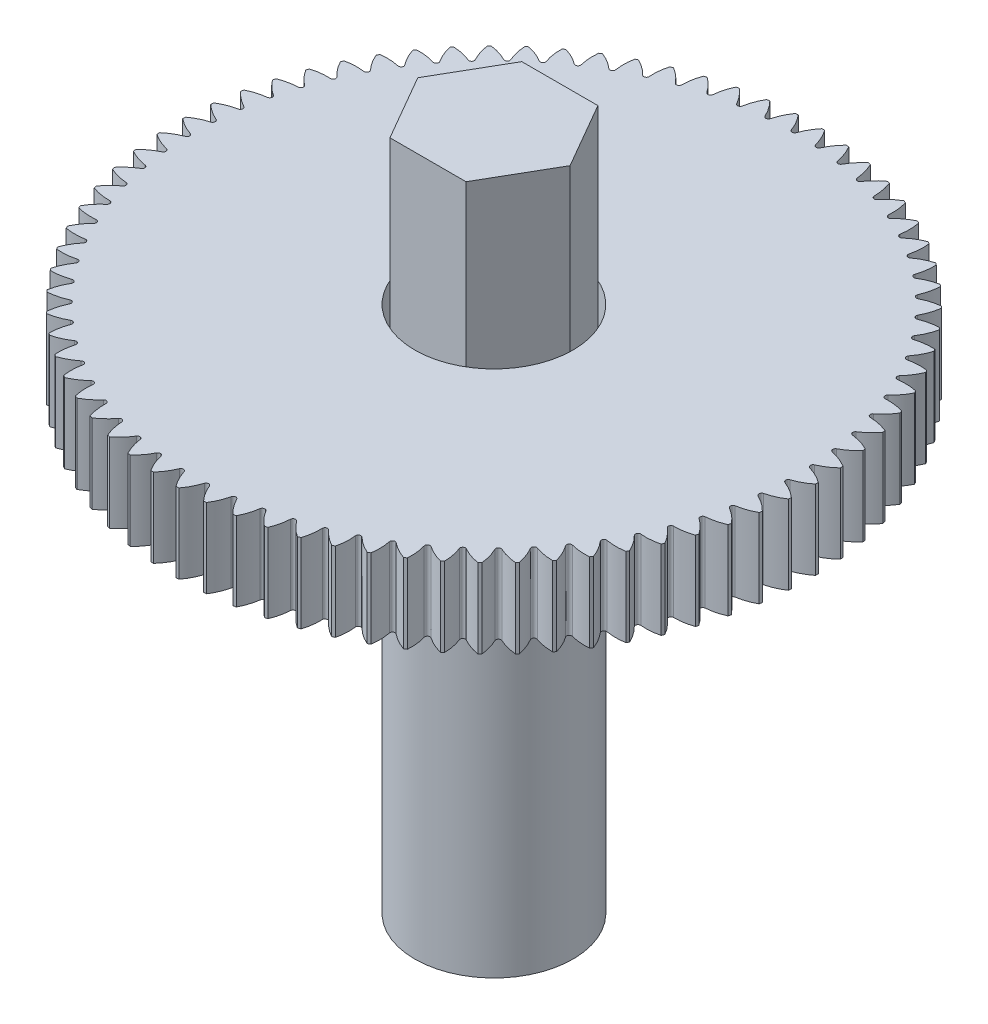
SolidWorks part; units mm, degrees
ref_plane "Front Plane" through (0, 0, 0) normal (0, 0, 1) x (1, 0, 0)
ref_plane "Top Plane" through (0, 0, 0) normal (0, 1, 0) x (1, 0, 0)
ref_plane "Right Plane" through (0, 0, 0) normal (1, 0, 0) x (0, 0, -1)
sketch "Sketch1" plane through (0, 0, 0) normal (0, 0, 1) x (1, 0, 0)
  line L0 (0, 13) -> (0, -13)
  line L1 (0, -13) -> (3, -13)
  line L2 (3, -13) -> (3, 4)
  line L3 (3, 4) -> (12, 4)
  line L4 (12, 4) -> (12, 7)
  line L5 (12, 7) -> (3, 7)
  line L6 (3, 7) -> (3, 13)
  line L7 (3, 13) -> (0, 13)
  point P9 (0, 0)
  dimension "D1" = 9
  dimension "D2" = 9
  dimension "D3" = 3
  dimension "D4" = 3
  dimension "D5" = 26
  dimension "D6" = 17
revolve "Revolve1" add sketch "Sketch1" angle 360 about L0
sketch "Sketch2" plane through (0, 7, 0) normal (0, 1, 0) x (1, 0, 0)
  line L0 (0, 13.9414) -> (0, 0) construction
  line L1 (-0.45, 11.9916) -> (0, 10.9916) construction
  line L2 (0, 10.9916) -> (0.45, 11.9916) construction
  line L3 (1.1666, 13.8925) -> (0, 0) construction
  line L4 (2.325, 13.7461) -> (0, 0) construction
  line L5 (3.4671, 13.5034) -> (0, 0) construction
  line L6 (4.5849, 13.1659) -> (0, 0) construction
  line L7 (5.6705, 12.7361) -> (0, 0) construction
  line L8 (6.7163, 12.2169) -> (0, 0) construction
  line L9 (7.715, 11.6121) -> (0, 0) construction
  line L10 (8.6597, 10.9258) -> (0, 0) construction
  line L11 (9.5435, 10.1628) -> (0, 0) construction
  line L12 (10.3605, 9.3286) -> (0, 0) construction
  line L13 (11.1047, 8.4289) -> (0, 0) construction
  line L14 (11.7711, 7.4702) -> (0, 0) construction
  line L15 (12.3549, 6.459) -> (0, 0) construction
  line L16 (12.852, 5.4025) -> (0, 0) construction
  line L17 (13.259, 4.3081) -> (0, 0) construction
  line L18 (13.573, 3.1835) -> (0, 0) construction
  line L19 (13.7918, 2.0366) -> (0, 0) construction
  line L20 (13.9139, 0.8754) -> (0, 0) construction
  line L21 (13.9383, -0.292) -> (0, 0) construction
  line L22 (13.865, -1.4573) -> (0, 0) construction
  line L23 (13.6944, -2.6124) -> (0, 0) construction
  line L24 (13.4278, -3.7491) -> (0, 0) construction
  line L25 (13.067, -4.8596) -> (0, 0) construction
  line L26 (12.6145, -5.9359) -> (0, 0) construction
  line L27 (12.0736, -6.9707) -> (0, 0) construction
  line L28 (11.4479, -7.9565) -> (0, 0) construction
  line L29 (10.742, -8.8866) -> (0, 0) construction
  line L30 (9.9607, -9.7543) -> (0, 0) construction
  line L31 (9.1096, -10.5536) -> (0, 0) construction
  line L32 (8.1945, -11.2788) -> (0, 0) construction
  line L33 (7.222, -11.925) -> (0, 0) construction
  line L34 (6.1988, -12.4875) -> (0, 0) construction
  line L35 (5.1322, -12.9624) -> (0, 0) construction
  line L36 (4.0295, -13.3464) -> (0, 0) construction
  line L37 (2.8986, -13.6367) -> (0, 0) construction
  line L38 (1.7473, -13.8314) -> (0, 0) construction
  line L39 (0.5838, -13.9291) -> (0, 0) construction
  line L40 (-0.5838, -13.9291) -> (0, 0) construction
  line L41 (-1.7473, -13.8314) -> (0, 0) construction
  line L42 (-2.8986, -13.6367) -> (0, 0) construction
  line L43 (-4.0295, -13.3464) -> (0, 0) construction
  line L44 (-5.1322, -12.9624) -> (0, 0) construction
  line L45 (-6.1988, -12.4875) -> (0, 0) construction
  line L46 (-7.222, -11.925) -> (0, 0) construction
  line L47 (-8.1945, -11.2788) -> (0, 0) construction
  line L48 (-9.1096, -10.5536) -> (0, 0) construction
  line L49 (-9.9607, -9.7543) -> (0, 0) construction
  line L50 (-10.742, -8.8866) -> (0, 0) construction
  line L51 (-11.4479, -7.9565) -> (0, 0) construction
  line L52 (-12.0736, -6.9707) -> (0, 0) construction
  line L53 (-12.6145, -5.9359) -> (0, 0) construction
  line L54 (-13.067, -4.8596) -> (0, 0) construction
  line L55 (-13.4278, -3.7491) -> (0, 0) construction
  line L56 (-13.6944, -2.6124) -> (0, 0) construction
  line L57 (-13.865, -1.4573) -> (0, 0) construction
  line L58 (-13.9383, -0.292) -> (0, 0) construction
  line L59 (-13.9139, 0.8754) -> (0, 0) construction
  line L60 (-13.7918, 2.0366) -> (0, 0) construction
  line L61 (-13.573, 3.1835) -> (0, 0) construction
  line L62 (-13.259, 4.3081) -> (0, 0) construction
  line L63 (-12.852, 5.4025) -> (0, 0) construction
  line L64 (-12.3549, 6.459) -> (0, 0) construction
  line L65 (-11.7711, 7.4702) -> (0, 0) construction
  line L66 (-11.1047, 8.4289) -> (0, 0) construction
  line L67 (-10.3605, 9.3286) -> (0, 0) construction
  line L68 (-9.5435, 10.1628) -> (0, 0) construction
  line L69 (-8.6597, 10.9258) -> (0, 0) construction
  line L70 (-7.715, 11.6121) -> (0, 0) construction
  line L71 (-6.7163, 12.2169) -> (0, 0) construction
  line L72 (-5.6705, 12.7361) -> (0, 0) construction
  line L73 (-4.5849, 13.1659) -> (0, 0) construction
  line L74 (-3.4671, 13.5034) -> (0, 0) construction
  line L75 (-2.325, 13.7461) -> (0, 0) construction
  line L76 (-1.1666, 13.8925) -> (0, 0) construction
  arc A0 (-0.45, 11.9916) -> (-0.0942, 11.3714) centre (-1.979, 10.7023) cw
  circle A1 centre (0, 0) radius 12
  arc A2 (0.45, 11.9916) -> (-0.45, 11.9916) centre (0, 0) ccw
  arc A3 (0.45, 11.9916) -> (0.0942, 11.3714) centre (1.979, 10.7023) ccw
  arc A4 (-0.0942, 11.3714) -> (0.0942, 11.3714) centre (0, 11.4049) ccw
  arc A5 (1.4518, 11.9118) -> (0.555, 11.9872) centre (0, 0) ccw
  arc A6 (0.555, 11.9872) -> (0.8576, 11.3394) centre (-1.0765, 10.8303) cw
  arc A7 (0.8576, 11.3394) -> (1.0454, 11.3237) centre (0.9543, 11.3649) ccw
  arc A8 (1.4518, 11.9118) -> (1.0454, 11.3237) centre (2.8676, 10.4991) ccw
  arc A9 (2.4435, 11.7486) -> (1.5561, 11.8987) centre (0, 0) ccw
  arc A10 (1.5561, 11.8987) -> (1.8035, 11.2279) centre (-0.1664, 10.8824) cw
  arc A11 (1.8035, 11.2279) -> (1.9893, 11.1965) centre (1.902, 11.2452) ccw
  arc A12 (2.4435, 11.7486) -> (1.9893, 11.1965) centre (3.7361, 10.2224) ccw
  arc A13 (3.418, 11.5029) -> (2.5463, 11.7267) centre (0, 0) ccw
  arc A14 (2.5463, 11.7267) -> (2.7367, 11.0376) centre (0.7448, 10.8582) cw
  arc A15 (2.7367, 11.0376) -> (2.9192, 10.9908) centre (2.8363, 11.0466) ccw
  arc A16 (3.418, 11.5029) -> (2.9192, 10.9908) centre (4.5783, 9.8739) ccw
  arc A17 (4.3686, 11.1766) -> (3.5187, 11.4725) centre (0, 0) ccw
  arc A18 (3.5187, 11.4725) -> (3.6507, 10.7699) centre (1.6507, 10.7578) cw
  arc A19 (3.6507, 10.7699) -> (3.8287, 10.7079) centre (3.7507, 10.7705) ccw
  arc A20 (4.3686, 11.1766) -> (3.8287, 10.7079) centre (5.3885, 9.4562) ccw
  arc A21 (5.2885, 10.7718) -> (4.4663, 11.1379) centre (0, 0) ccw
  arc A22 (4.4663, 11.1379) -> (4.5391, 10.4267) centre (2.5451, 10.5819) cw
  arc A23 (4.5391, 10.4267) -> (4.7113, 10.35) centre (4.6388, 10.4189) ccw
  arc A24 (5.2885, 10.7718) -> (4.7113, 10.35) centre (6.1609, 8.9721) ccw
  arc A25 (6.1713, 10.2915) -> (5.3826, 10.7251) centre (0, 0) ccw
  arc A26 (5.3826, 10.7251) -> (5.3957, 10.0103) centre (3.4217, 10.3318) cw
  arc A27 (5.3957, 10.0103) -> (5.5608, 9.9195) centre (5.4944, 9.9942) ccw
  arc A28 (6.1713, 10.2915) -> (5.5608, 9.9195) centre (6.89, 8.4251) ccw
  arc A29 (7.0108, 9.739) -> (6.2612, 10.2371) centre (0, 0) ccw
  arc A30 (6.2612, 10.2371) -> (6.2144, 9.5237) centre (4.2742, 10.0093) cw
  arc A31 (6.2144, 9.5237) -> (6.3714, 9.4194) centre (6.3114, 9.4994) ccw
  arc A32 (7.0108, 9.739) -> (6.3714, 9.4194) centre (7.5709, 7.819) ccw
  arc A33 (7.8012, 9.1182) -> (7.0959, 9.6772) centre (0, 0) ccw
  arc A34 (7.0959, 9.6772) -> (6.9895, 8.9703) centre (5.0968, 9.6165) cw
  arc A35 (6.9895, 8.9703) -> (7.1372, 8.8532) centre (7.0841, 8.9379) ccw
  arc A36 (7.8012, 9.1182) -> (7.1372, 8.8532) centre (8.1986, 7.1581) ccw
  arc A37 (8.5368, 8.4334) -> (7.8808, 9.0495) centre (0, 0) ccw
  arc A38 (7.8808, 9.0495) -> (7.7156, 8.3539) centre (5.8836, 9.1563) cw
  arc A39 (7.7156, 8.3539) -> (7.853, 8.2249) centre (7.8072, 8.3138) ccw
  arc A40 (8.5368, 8.4334) -> (7.853, 8.2249) centre (8.7688, 6.4469) ccw
  arc A41 (9.2126, 7.6895) -> (8.6104, 8.3583) centre (0, 0) ccw
  arc A42 (8.6104, 8.3583) -> (8.3876, 7.679) centre (6.6292, 8.6319) cw
  arc A43 (8.3876, 7.679) -> (8.5137, 7.5389) centre (8.4755, 7.6314) ccw
  arc A44 (9.2126, 7.6895) -> (8.5137, 7.5389) centre (9.2775, 5.6906) ccw
  arc A45 (9.8237, 6.8916) -> (9.2796, 7.6085) centre (0, 0) ccw
  arc A46 (9.2796, 7.6085) -> (9.0007, 6.9502) centre (7.3282, 8.0469) cw
  arc A47 (9.0007, 6.9502) -> (9.1147, 6.8001) centre (9.0843, 6.8954) ccw
  arc A48 (9.8237, 6.8916) -> (9.1147, 6.8001) centre (9.7212, 4.8943) ccw
  arc A49 (10.3659, 6.0455) -> (9.8837, 6.8053) centre (0, 0) ccw
  arc A50 (9.8837, 6.8053) -> (9.5507, 6.1727) centre (7.9758, 7.4055) cw
  arc A51 (9.5507, 6.1727) -> (9.6517, 6.0136) centre (9.6295, 6.1111) ccw
  arc A52 (10.3659, 6.0455) -> (9.6517, 6.0136) centre (10.0966, 4.0637) ccw
  arc A53 (10.8354, 5.1569) -> (10.4185, 5.9544) centre (0, 0) ccw
  arc A54 (10.4185, 5.9544) -> (10.0338, 5.3519) centre (8.5675, 6.7121) cw
  arc A55 (10.0338, 5.3519) -> (10.1211, 5.1848) centre (10.1071, 5.2838) ccw
  arc A56 (10.8354, 5.1569) -> (10.1211, 5.1848) centre (10.4012, 3.2046) ccw
  arc A57 (11.229, 4.2321) -> (10.8802, 5.0618) centre (0, 0) ccw
  arc A58 (10.8802, 5.0618) -> (10.4464, 4.4935) centre (9.0992, 5.9716) cw
  arc A59 (10.4464, 4.4935) -> (10.5194, 4.3197) centre (10.5138, 4.4196) ccw
  arc A60 (11.229, 4.2321) -> (10.5194, 4.3197) centre (10.6329, 2.323) ccw
  arc A61 (11.5437, 3.2776) -> (11.2656, 4.1336) centre (0, 0) ccw
  arc A62 (11.2656, 4.1336) -> (10.7858, 3.6036) centre (9.5669, 5.1893) cw
  arc A63 (10.7858, 3.6036) -> (10.844, 3.4243) centre (10.8467, 3.5243) ccw
  arc A64 (11.5437, 3.2776) -> (10.844, 3.4243) centre (10.79, 1.4251) ccw
  arc A65 (11.7775, 2.3002) -> (11.572, 3.1764) centre (0, 0) ccw
  arc A66 (11.572, 3.1764) -> (11.0495, 2.6884) centre (9.9676, 4.3706) cw
  arc A67 (11.0495, 2.6884) -> (11.0925, 2.5049) centre (11.1036, 2.6043) ccw
  arc A68 (11.7775, 2.3002) -> (11.0925, 2.5049) centre (10.8714, 0.5172) ccw
  arc A69 (11.9287, 1.3066) -> (11.7972, 2.1969) centre (0, 0) ccw
  arc A70 (11.7972, 2.1969) -> (11.2357, 1.7544) centre (10.2984, 3.5212) cw
  arc A71 (11.2357, 1.7544) -> (11.2632, 1.5679) centre (11.2826, 1.6661) ccw
  arc A72 (11.9287, 1.3066) -> (11.2632, 1.5679) centre (10.8766, -0.3943) ccw
  arc A73 (11.9962, 0.3038) -> (11.9396, 1.2021) centre (0, 0) ccw
  arc A74 (11.9396, 1.2021) -> (11.3431, 0.8081) centre (10.5569, 2.6471) cw
  arc A75 (11.3431, 0.8081) -> (11.3549, 0.62) centre (11.3824, 0.7161) ccw
  arc A76 (11.9962, 0.3038) -> (11.3549, 0.62) centre (10.8054, -1.3031) ccw
  arc A77 (11.9795, -0.701) -> (11.9984, 0.1988) centre (0, 0) ccw
  arc A78 (11.9984, 0.1988) -> (11.3709, -0.1439) centre (10.7414, 1.7544) cw
  arc A79 (11.3709, -0.1439) -> (11.367, -0.3324) centre (11.4024, -0.2388) ccw
  arc A80 (11.9795, -0.701) -> (11.367, -0.3324) centre (10.6585, -2.2027) ccw
  arc A81 (11.8788, -1.701) -> (11.9729, -0.8059) centre (0, 0) ccw
  arc A82 (11.9729, -0.8059) -> (11.319, -1.0949) centre (10.8505, 0.8494) cw
  arc A83 (11.319, -1.0949) -> (11.2993, -1.2824) centre (11.3424, -1.1921) ccw
  arc A84 (11.8788, -1.701) -> (11.2993, -1.2824) centre (10.4368, -3.0868) ccw
  arc A85 (11.6948, -2.689) -> (11.8635, -1.805) centre (0, 0) ccw
  arc A86 (11.8635, -1.805) -> (11.1877, -2.0382) centre (10.8835, -0.0615) cw
  arc A87 (11.1877, -2.0382) -> (11.1524, -2.2234) centre (11.2029, -2.1371) ccw
  arc A88 (11.6948, -2.689) -> (11.1524, -2.2234) centre (10.1419, -3.9493) ccw
  arc A89 (11.4288, -3.6582) -> (11.6708, -2.7913) centre (0, 0) ccw
  arc A90 (11.6708, -2.7913) -> (10.9779, -2.9672) centre (10.8402, -0.972) cw
  arc A91 (10.9779, -2.9672) -> (10.9272, -3.1488) centre (10.9848, -3.067) ccw
  arc A92 (11.4288, -3.6582) -> (10.9272, -3.1488) centre (9.7758, -4.7841) ccw
  arc A93 (11.0826, -4.6017) -> (11.3963, -3.7581) centre (0, 0) ccw
  arc A94 (11.3963, -3.7581) -> (10.6911, -3.8754) centre (10.7209, -1.8757) cw
  arc A95 (10.6911, -3.8754) -> (10.6254, -4.0521) centre (10.6896, -3.9754) ccw
  arc A96 (11.0826, -4.6017) -> (10.6254, -4.0521) centre (9.3412, -5.5854) ccw
  arc A97 (10.6587, -5.5129) -> (11.0419, -4.6986) centre (0, 0) ccw
  arc A98 (11.0419, -4.6986) -> (10.3293, -4.7565) centre (10.5263, -2.7662) cw
  arc A99 (10.3293, -4.7565) -> (10.2491, -4.927) centre (10.3195, -4.856) ccw
  arc A100 (10.6587, -5.5129) -> (10.2491, -4.927) centre (8.8411, -6.3474) ccw
  arc A101 (10.16, -6.3855) -> (10.61, -5.6061) centre (0, 0) ccw
  arc A102 (10.61, -5.6061) -> (9.8951, -5.6041) centre (10.2579, -3.6373) cw
  arc A103 (9.8951, -5.6041) -> (9.8008, -5.7673) centre (9.8769, -5.7025) ccw
  arc A104 (10.16, -6.3855) -> (9.8008, -5.7673) centre (8.279, -7.065) ccw
  arc A105 (9.59, -7.2133) -> (10.1037, -6.4742) centre (0, 0) ccw
  arc A106 (10.1037, -6.4742) -> (9.3914, -6.4125) centre (9.9176, -4.4829) cw
  arc A107 (9.3914, -6.4125) -> (9.2839, -6.5672) centre (9.3651, -6.5089) ccw
  arc A108 (9.59, -7.2133) -> (9.2839, -6.5672) centre (7.6587, -7.733) ccw
  arc A109 (8.9528, -7.9904) -> (9.5265, -7.297) centre (0, 0) ccw
  arc A110 (9.5265, -7.297) -> (8.8219, -7.1758) centre (9.5077, -5.2971) cw
  arc A111 (8.8219, -7.1758) -> (8.7018, -7.321) centre (8.7876, -7.2698) ccw
  arc A112 (8.9528, -7.9904) -> (8.7018, -7.321) centre (6.9848, -8.3467) ccw
  arc A113 (8.2528, -8.7116) -> (8.8825, -8.0685) centre (0, 0) ccw
  arc A114 (8.8825, -8.0685) -> (8.1905, -7.8889) centre (9.0311, -6.0741) cw
  arc A115 (8.1905, -7.8889) -> (8.0587, -8.0235) centre (8.1485, -7.9796) ccw
  arc A116 (8.2528, -8.7116) -> (8.0587, -8.0235) centre (6.2619, -8.9019) ccw
  arc A117 (7.4949, -9.3716) -> (8.1762, -8.7835) centre (0, 0) ccw
  arc A118 (8.1762, -8.7835) -> (7.5017, -8.5466) centre (8.4912, -6.8085) cw
  arc A119 (7.5017, -8.5466) -> (7.359, -8.6697) centre (7.4522, -8.6335) ccw
  arc A120 (7.4949, -9.3716) -> (7.359, -8.6697) centre (5.495, -9.3947) ccw
  arc A121 (6.6844, -9.9659) -> (7.4125, -9.4369) centre (0, 0) ccw
  arc A122 (7.4125, -9.4369) -> (6.7602, -9.1443) centre (7.8917, -7.4951) cw
  arc A123 (6.7602, -9.1443) -> (6.6077, -9.2551) centre (6.7036, -9.2268) ccw
  arc A124 (6.6844, -9.9659) -> (6.6077, -9.2551) centre (4.6896, -9.8215) ccw
  arc A125 (5.827, -10.4903) -> (6.5969, -10.024) centre (0, 0) ccw
  arc A126 (6.5969, -10.024) -> (5.9713, -9.6779) centre (7.2368, -8.1292) cw
  arc A127 (5.9713, -9.6779) -> (5.8101, -9.7755) centre (5.908, -9.7553) ccw
  arc A128 (5.827, -10.4903) -> (5.8101, -9.7755) centre (3.8513, -10.1795) ccw
  arc A129 (4.9288, -10.9411) -> (5.7349, -10.5409) centre (0, 0) ccw
  arc A130 (5.7349, -10.5409) -> (5.1406, -10.1436) centre (6.5312, -8.7062) cw
  arc A131 (5.1406, -10.1436) -> (4.9717, -10.2274) centre (5.071, -10.2155) ccw
  arc A132 (4.9288, -10.9411) -> (4.9717, -10.2274) centre (2.986, -10.4661) ccw
  arc A133 (3.996, -11.3151) -> (4.8328, -10.9838) centre (0, 0) ccw
  arc A134 (4.8328, -10.9838) -> (4.2737, -10.5382) centre (5.7798, -9.2222) cw
  arc A135 (4.2737, -10.5382) -> (4.0985, -10.6076) centre (4.1984, -10.604) ccw
  arc A136 (3.996, -11.3151) -> (4.0985, -10.6076) centre (2.0998, -10.6792) ccw
  arc A137 (3.0351, -11.6098) -> (3.8967, -11.3497) centre (0, 0) ccw
  arc A138 (3.8967, -11.3497) -> (3.3769, -10.8589) centre (4.9878, -9.6735) cw
  arc A139 (3.3769, -10.8589) -> (3.1965, -10.9133) centre (3.2964, -10.9181) ccw
  arc A140 (3.0351, -11.6098) -> (3.1965, -10.9133) centre (1.1988, -10.8175) ccw
  arc A141 (2.053, -11.8231) -> (2.9334, -11.636) centre (0, 0) ccw
  arc A142 (2.9334, -11.636) -> (2.4564, -11.1034) centre (4.1609, -10.057) cw
  arc A143 (2.4564, -11.1034) -> (2.2721, -11.1425) centre (2.3712, -11.1557) ccw
  arc A144 (2.053, -11.8231) -> (2.2721, -11.1425) centre (0.2894, -10.8799) ccw
  arc A145 (1.0565, -11.9534) -> (1.9494, -11.8406) centre (0, 0) ccw
  arc A146 (1.9494, -11.8406) -> (1.5187, -11.27) centre (3.3047, -10.3699) cw
  arc A147 (1.5187, -11.27) -> (1.3317, -11.2936) centre (1.4294, -11.315) ccw
  arc A148 (1.0565, -11.9534) -> (1.3317, -11.2936) centre (-0.622, -10.8659) ccw
  arc A149 (0.0525, -11.9999) -> (0.9518, -11.9622) centre (0, 0) ccw
  arc A150 (0.9518, -11.9622) -> (0.5703, -11.3575) centre (2.4254, -10.61) cw
  arc A151 (0.5703, -11.3575) -> (0.382, -11.3654) centre (0.4776, -11.3949) ccw
  arc A152 (0.0525, -11.9999) -> (0.382, -11.3654) centre (-1.5291, -10.7758) ccw
  arc A153 (-0.9518, -11.9622) -> (-0.0525, -11.9999) centre (0, 0) ccw
  arc A154 (-0.0525, -11.9999) -> (-0.382, -11.3654) centre (1.5291, -10.7758) cw
  arc A155 (-0.382, -11.3654) -> (-0.5703, -11.3575) centre (-0.4776, -11.3949) ccw
  arc A156 (-0.9518, -11.9622) -> (-0.5703, -11.3575) centre (-2.4254, -10.61) ccw
  arc A157 (-1.9494, -11.8406) -> (-1.0565, -11.9534) centre (0, 0) ccw
  arc A158 (-1.0565, -11.9534) -> (-1.3317, -11.2936) centre (0.622, -10.8659) cw
  arc A159 (-1.3317, -11.2936) -> (-1.5187, -11.27) centre (-1.4294, -11.315) ccw
  arc A160 (-1.9494, -11.8406) -> (-1.5187, -11.27) centre (-3.3047, -10.3699) ccw
  arc A161 (-2.9334, -11.636) -> (-2.053, -11.8231) centre (0, 0) ccw
  arc A162 (-2.053, -11.8231) -> (-2.2721, -11.1425) centre (-0.2894, -10.8799) cw
  arc A163 (-2.2721, -11.1425) -> (-2.4564, -11.1034) centre (-2.3712, -11.1557) ccw
  arc A164 (-2.9334, -11.636) -> (-2.4564, -11.1034) centre (-4.1609, -10.057) ccw
  arc A165 (-3.8967, -11.3497) -> (-3.0351, -11.6098) centre (0, 0) ccw
  arc A166 (-3.0351, -11.6098) -> (-3.1965, -10.9133) centre (-1.1988, -10.8175) cw
  arc A167 (-3.1965, -10.9133) -> (-3.3769, -10.8589) centre (-3.2964, -10.9181) ccw
  arc A168 (-3.8967, -11.3497) -> (-3.3769, -10.8589) centre (-4.9878, -9.6735) ccw
  arc A169 (-4.8328, -10.9838) -> (-3.996, -11.3151) centre (0, 0) ccw
  arc A170 (-3.996, -11.3151) -> (-4.0985, -10.6076) centre (-2.0998, -10.6792) cw
  arc A171 (-4.0985, -10.6076) -> (-4.2737, -10.5382) centre (-4.1984, -10.604) ccw
  arc A172 (-4.8328, -10.9838) -> (-4.2737, -10.5382) centre (-5.7798, -9.2222) ccw
  arc A173 (-5.7349, -10.5409) -> (-4.9288, -10.9411) centre (0, 0) ccw
  arc A174 (-4.9288, -10.9411) -> (-4.9717, -10.2274) centre (-2.986, -10.4661) cw
  arc A175 (-4.9717, -10.2274) -> (-5.1406, -10.1436) centre (-5.071, -10.2155) ccw
  arc A176 (-5.7349, -10.5409) -> (-5.1406, -10.1436) centre (-6.5312, -8.7062) ccw
  arc A177 (-6.5969, -10.024) -> (-5.827, -10.4903) centre (0, 0) ccw
  arc A178 (-5.827, -10.4903) -> (-5.8101, -9.7755) centre (-3.8513, -10.1795) cw
  arc A179 (-5.8101, -9.7755) -> (-5.9713, -9.6779) centre (-5.908, -9.7553) ccw
  arc A180 (-6.5969, -10.024) -> (-5.9713, -9.6779) centre (-7.2368, -8.1292) ccw
  arc A181 (-7.4125, -9.4369) -> (-6.6844, -9.9659) centre (0, 0) ccw
  arc A182 (-6.6844, -9.9659) -> (-6.6077, -9.2551) centre (-4.6896, -9.8215) cw
  arc A183 (-6.6077, -9.2551) -> (-6.7602, -9.1443) centre (-6.7036, -9.2268) ccw
  arc A184 (-7.4125, -9.4369) -> (-6.7602, -9.1443) centre (-7.8917, -7.4951) ccw
  arc A185 (-8.1762, -8.7835) -> (-7.4949, -9.3716) centre (0, 0) ccw
  arc A186 (-7.4949, -9.3716) -> (-7.359, -8.6697) centre (-5.495, -9.3947) cw
  arc A187 (-7.359, -8.6697) -> (-7.5017, -8.5466) centre (-7.4522, -8.6335) ccw
  arc A188 (-8.1762, -8.7835) -> (-7.5017, -8.5466) centre (-8.4912, -6.8085) ccw
  arc A189 (-8.8825, -8.0685) -> (-8.2528, -8.7116) centre (0, 0) ccw
  arc A190 (-8.2528, -8.7116) -> (-8.0587, -8.0235) centre (-6.2619, -8.9019) cw
  arc A191 (-8.0587, -8.0235) -> (-8.1905, -7.8889) centre (-8.1485, -7.9796) ccw
  arc A192 (-8.8825, -8.0685) -> (-8.1905, -7.8889) centre (-9.0311, -6.0741) ccw
  arc A193 (-9.5265, -7.297) -> (-8.9528, -7.9904) centre (0, 0) ccw
  arc A194 (-8.9528, -7.9904) -> (-8.7018, -7.321) centre (-6.9848, -8.3467) cw
  arc A195 (-8.7018, -7.321) -> (-8.8219, -7.1758) centre (-8.7876, -7.2698) ccw
  arc A196 (-9.5265, -7.297) -> (-8.8219, -7.1758) centre (-9.5077, -5.2971) ccw
  arc A197 (-10.1037, -6.4742) -> (-9.59, -7.2133) centre (0, 0) ccw
  arc A198 (-9.59, -7.2133) -> (-9.2839, -6.5672) centre (-7.6587, -7.733) cw
  arc A199 (-9.2839, -6.5672) -> (-9.3914, -6.4125) centre (-9.3651, -6.5089) ccw
  arc A200 (-10.1037, -6.4742) -> (-9.3914, -6.4125) centre (-9.9176, -4.4829) ccw
  arc A201 (-10.61, -5.6061) -> (-10.16, -6.3855) centre (0, 0) ccw
  arc A202 (-10.16, -6.3855) -> (-9.8008, -5.7673) centre (-8.279, -7.065) cw
  arc A203 (-9.8008, -5.7673) -> (-9.8951, -5.6041) centre (-9.8769, -5.7025) ccw
  arc A204 (-10.61, -5.6061) -> (-9.8951, -5.6041) centre (-10.2579, -3.6373) ccw
  arc A205 (-11.0419, -4.6986) -> (-10.6587, -5.5129) centre (0, 0) ccw
  arc A206 (-10.6587, -5.5129) -> (-10.2491, -4.927) centre (-8.8411, -6.3474) cw
  arc A207 (-10.2491, -4.927) -> (-10.3293, -4.7565) centre (-10.3195, -4.856) ccw
  arc A208 (-11.0419, -4.6986) -> (-10.3293, -4.7565) centre (-10.5263, -2.7662) ccw
  arc A209 (-11.3963, -3.7581) -> (-11.0826, -4.6017) centre (0, 0) ccw
  arc A210 (-11.0826, -4.6017) -> (-10.6254, -4.0521) centre (-9.3412, -5.5854) cw
  arc A211 (-10.6254, -4.0521) -> (-10.6911, -3.8754) centre (-10.6896, -3.9754) ccw
  arc A212 (-11.3963, -3.7581) -> (-10.6911, -3.8754) centre (-10.7209, -1.8757) ccw
  arc A213 (-11.6708, -2.7913) -> (-11.4288, -3.6582) centre (0, 0) ccw
  arc A214 (-11.4288, -3.6582) -> (-10.9272, -3.1488) centre (-9.7758, -4.7841) cw
  arc A215 (-10.9272, -3.1488) -> (-10.9779, -2.9672) centre (-10.9848, -3.067) ccw
  arc A216 (-11.6708, -2.7913) -> (-10.9779, -2.9672) centre (-10.8402, -0.972) ccw
  arc A217 (-11.8635, -1.805) -> (-11.6948, -2.689) centre (0, 0) ccw
  arc A218 (-11.6948, -2.689) -> (-11.1524, -2.2234) centre (-10.1419, -3.9493) cw
  arc A219 (-11.1524, -2.2234) -> (-11.1877, -2.0382) centre (-11.2029, -2.1371) ccw
  arc A220 (-11.8635, -1.805) -> (-11.1877, -2.0382) centre (-10.8835, -0.0615) ccw
  arc A221 (-11.9729, -0.8059) -> (-11.8788, -1.701) centre (0, 0) ccw
  arc A222 (-11.8788, -1.701) -> (-11.2993, -1.2824) centre (-10.4368, -3.0868) cw
  arc A223 (-11.2993, -1.2824) -> (-11.319, -1.0949) centre (-11.3424, -1.1921) ccw
  arc A224 (-11.9729, -0.8059) -> (-11.319, -1.0949) centre (-10.8505, 0.8494) ccw
  arc A225 (-11.9984, 0.1988) -> (-11.9795, -0.701) centre (0, 0) ccw
  arc A226 (-11.9795, -0.701) -> (-11.367, -0.3324) centre (-10.6585, -2.2027) cw
  arc A227 (-11.367, -0.3324) -> (-11.3709, -0.1439) centre (-11.4024, -0.2388) ccw
  arc A228 (-11.9984, 0.1988) -> (-11.3709, -0.1439) centre (-10.7414, 1.7544) ccw
  arc A229 (-11.9396, 1.2021) -> (-11.9962, 0.3038) centre (0, 0) ccw
  arc A230 (-11.9962, 0.3038) -> (-11.3549, 0.62) centre (-10.8054, -1.3031) cw
  arc A231 (-11.3549, 0.62) -> (-11.3431, 0.8081) centre (-11.3824, 0.7161) ccw
  arc A232 (-11.9396, 1.2021) -> (-11.3431, 0.8081) centre (-10.5569, 2.6471) ccw
  arc A233 (-11.7972, 2.1969) -> (-11.9287, 1.3066) centre (0, 0) ccw
  arc A234 (-11.9287, 1.3066) -> (-11.2632, 1.5679) centre (-10.8766, -0.3943) cw
  arc A235 (-11.2632, 1.5679) -> (-11.2357, 1.7544) centre (-11.2826, 1.6661) ccw
  arc A236 (-11.7972, 2.1969) -> (-11.2357, 1.7544) centre (-10.2984, 3.5212) ccw
  arc A237 (-11.572, 3.1764) -> (-11.7775, 2.3002) centre (0, 0) ccw
  arc A238 (-11.7775, 2.3002) -> (-11.0925, 2.5049) centre (-10.8714, 0.5172) cw
  arc A239 (-11.0925, 2.5049) -> (-11.0495, 2.6884) centre (-11.1036, 2.6043) ccw
  arc A240 (-11.572, 3.1764) -> (-11.0495, 2.6884) centre (-9.9676, 4.3706) ccw
  arc A241 (-11.2656, 4.1336) -> (-11.5437, 3.2776) centre (0, 0) ccw
  arc A242 (-11.5437, 3.2776) -> (-10.844, 3.4243) centre (-10.79, 1.4251) cw
  arc A243 (-10.844, 3.4243) -> (-10.7858, 3.6036) centre (-10.8467, 3.5243) ccw
  arc A244 (-11.2656, 4.1336) -> (-10.7858, 3.6036) centre (-9.5669, 5.1893) ccw
  arc A245 (-10.8802, 5.0618) -> (-11.229, 4.2321) centre (0, 0) ccw
  arc A246 (-11.229, 4.2321) -> (-10.5194, 4.3197) centre (-10.6329, 2.323) cw
  arc A247 (-10.5194, 4.3197) -> (-10.4464, 4.4935) centre (-10.5138, 4.4196) ccw
  arc A248 (-10.8802, 5.0618) -> (-10.4464, 4.4935) centre (-9.0992, 5.9716) ccw
  arc A249 (-10.4185, 5.9544) -> (-10.8354, 5.1569) centre (0, 0) ccw
  arc A250 (-10.8354, 5.1569) -> (-10.1211, 5.1848) centre (-10.4012, 3.2046) cw
  arc A251 (-10.1211, 5.1848) -> (-10.0338, 5.3519) centre (-10.1071, 5.2838) ccw
  arc A252 (-10.4185, 5.9544) -> (-10.0338, 5.3519) centre (-8.5675, 6.7121) ccw
  arc A253 (-9.8837, 6.8053) -> (-10.3659, 6.0455) centre (0, 0) ccw
  arc A254 (-10.3659, 6.0455) -> (-9.6517, 6.0136) centre (-10.0966, 4.0637) cw
  arc A255 (-9.6517, 6.0136) -> (-9.5507, 6.1727) centre (-9.6295, 6.1111) ccw
  arc A256 (-9.8837, 6.8053) -> (-9.5507, 6.1727) centre (-7.9758, 7.4055) ccw
  arc A257 (-9.2796, 7.6085) -> (-9.8237, 6.8916) centre (0, 0) ccw
  arc A258 (-9.8237, 6.8916) -> (-9.1147, 6.8001) centre (-9.7212, 4.8943) cw
  arc A259 (-9.1147, 6.8001) -> (-9.0007, 6.9502) centre (-9.0843, 6.8954) ccw
  arc A260 (-9.2796, 7.6085) -> (-9.0007, 6.9502) centre (-7.3282, 8.0469) ccw
  arc A261 (-8.6104, 8.3583) -> (-9.2126, 7.6895) centre (0, 0) ccw
  arc A262 (-9.2126, 7.6895) -> (-8.5137, 7.5389) centre (-9.2775, 5.6906) cw
  arc A263 (-8.5137, 7.5389) -> (-8.3876, 7.679) centre (-8.4755, 7.6314) ccw
  arc A264 (-8.6104, 8.3583) -> (-8.3876, 7.679) centre (-6.6292, 8.6319) ccw
  arc A265 (-7.8808, 9.0495) -> (-8.5368, 8.4334) centre (0, 0) ccw
  arc A266 (-8.5368, 8.4334) -> (-7.853, 8.2249) centre (-8.7688, 6.4469) cw
  arc A267 (-7.853, 8.2249) -> (-7.7156, 8.3539) centre (-7.8072, 8.3138) ccw
  arc A268 (-7.8808, 9.0495) -> (-7.7156, 8.3539) centre (-5.8836, 9.1563) ccw
  arc A269 (-7.0959, 9.6772) -> (-7.8012, 9.1182) centre (0, 0) ccw
  arc A270 (-7.8012, 9.1182) -> (-7.1372, 8.8532) centre (-8.1986, 7.1581) cw
  arc A271 (-7.1372, 8.8532) -> (-6.9895, 8.9703) centre (-7.0841, 8.9379) ccw
  arc A272 (-7.0959, 9.6772) -> (-6.9895, 8.9703) centre (-5.0968, 9.6165) ccw
  arc A273 (-6.2612, 10.2371) -> (-7.0108, 9.739) centre (0, 0) ccw
  arc A274 (-7.0108, 9.739) -> (-6.3714, 9.4194) centre (-7.5709, 7.819) cw
  arc A275 (-6.3714, 9.4194) -> (-6.2144, 9.5237) centre (-6.3114, 9.4994) ccw
  arc A276 (-6.2612, 10.2371) -> (-6.2144, 9.5237) centre (-4.2742, 10.0093) ccw
  arc A277 (-5.3826, 10.7251) -> (-6.1713, 10.2915) centre (0, 0) ccw
  arc A278 (-6.1713, 10.2915) -> (-5.5608, 9.9195) centre (-6.89, 8.4251) cw
  arc A279 (-5.5608, 9.9195) -> (-5.3957, 10.0103) centre (-5.4944, 9.9942) ccw
  arc A280 (-5.3826, 10.7251) -> (-5.3957, 10.0103) centre (-3.4217, 10.3318) ccw
  arc A281 (-4.4663, 11.1379) -> (-5.2885, 10.7718) centre (0, 0) ccw
  arc A282 (-5.2885, 10.7718) -> (-4.7113, 10.35) centre (-6.1609, 8.9721) cw
  arc A283 (-4.7113, 10.35) -> (-4.5391, 10.4267) centre (-4.6388, 10.4189) ccw
  arc A284 (-4.4663, 11.1379) -> (-4.5391, 10.4267) centre (-2.5451, 10.5819) ccw
  arc A285 (-3.5187, 11.4725) -> (-4.3686, 11.1766) centre (0, 0) ccw
  arc A286 (-4.3686, 11.1766) -> (-3.8287, 10.7079) centre (-5.3885, 9.4562) cw
  arc A287 (-3.8287, 10.7079) -> (-3.6507, 10.7699) centre (-3.7507, 10.7705) ccw
  arc A288 (-3.5187, 11.4725) -> (-3.6507, 10.7699) centre (-1.6507, 10.7578) ccw
  arc A289 (-2.5463, 11.7267) -> (-3.418, 11.5029) centre (0, 0) ccw
  arc A290 (-3.418, 11.5029) -> (-2.9192, 10.9908) centre (-4.5783, 9.8739) cw
  arc A291 (-2.9192, 10.9908) -> (-2.7367, 11.0376) centre (-2.8363, 11.0466) ccw
  arc A292 (-2.5463, 11.7267) -> (-2.7367, 11.0376) centre (-0.7448, 10.8582) ccw
  arc A293 (-1.5561, 11.8987) -> (-2.4435, 11.7486) centre (0, 0) ccw
  arc A294 (-2.4435, 11.7486) -> (-1.9893, 11.1965) centre (-3.7361, 10.2224) cw
  arc A295 (-1.9893, 11.1965) -> (-1.8035, 11.2279) centre (-1.902, 11.2452) ccw
  arc A296 (-1.5561, 11.8987) -> (-1.8035, 11.2279) centre (0.1664, 10.8824) ccw
  arc A297 (-0.555, 11.9872) -> (-1.4518, 11.9118) centre (0, 0) ccw
  arc A298 (-1.4518, 11.9118) -> (-1.0454, 11.3237) centre (-2.8676, 10.4991) cw
  arc A299 (-1.0454, 11.3237) -> (-0.8576, 11.3394) centre (-0.9543, 11.3649) ccw
  arc A300 (-0.555, 11.9872) -> (-0.8576, 11.3394) centre (1.0765, 10.8303) ccw
  point P4 (0, 12)
  point P607 (0, 0)
  dimension "D4" = 2
  dimension "D5" = 2
  dimension "D6" = 0.1
  dimension "D2" = 0.45
  dimension "D3" = 1
  dimension "D1" = 0
  dimension "D7" = 75
extrude "Cut-Extrude1" cut sketch "Sketch2" against normal up to surface (3 mm away) up to face at (0, 4, 12)
sketch "Sketch7" plane through (0, 13, 0) normal (0, 1, 0) x (1, 0, 0)
  line L1 (1.4434, -2.5) -> (2.8868, 0)
  line L2 (2.8868, 0) -> (1.4434, 2.5)
  line L3 (1.4434, 2.5) -> (-1.4434, 2.5)
  line L4 (-1.4434, 2.5) -> (-2.8868, 0)
  line L5 (-2.8868, 0) -> (-1.4434, -2.5)
  line L6 (-1.4434, -2.5) -> (1.4434, -2.5)
  circle A0 centre (0, 0) radius 2.5 construction
  circle A1 centre (0, 0) radius 3 construction
  circle A2 centre (0, 0) radius 3
  point P11 (0, 2.5)
  dimension "D1" = 5
extrude "Cut-Extrude9" cut sketch "Sketch7" against normal blind 9
